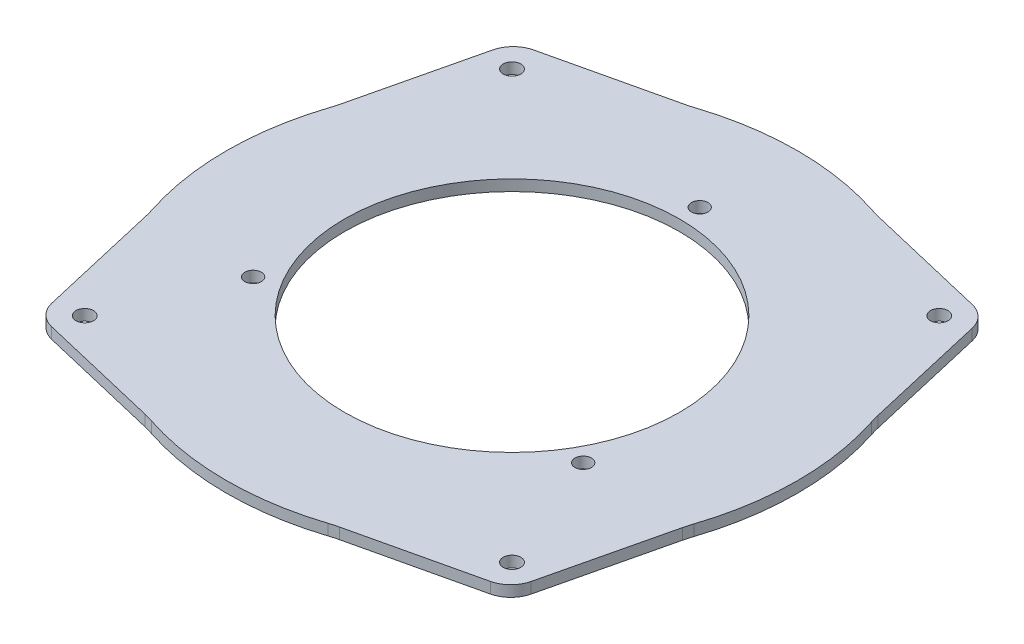
SolidWorks part; units mm, degrees
ref_plane "Front Plane" through (0, 0, 0) normal (0, 0, 1) x (1, 0, 0)
ref_plane "Top Plane" through (0, 0, 0) normal (0, 1, 0) x (1, 0, 0)
ref_plane "Right Plane" through (0, 0, 0) normal (1, 0, 0) x (0, 0, -1)
sketch "Sketch1" plane through (0, 0, 0) normal (0, 1, 0) x (1, 0, 0)
  line L0 (49.872, -261.8935) -> (473.872, -261.8935) construction
  line L1 (17.8971, 48.9297) -> (40.1493, 43.6512)
  line L2 (43.8664, 39.9141) -> (49.0252, 17.6338)
  line L3 (48.9297, -17.8971) -> (43.6512, -40.1493)
  line L4 (39.9141, -43.8664) -> (17.6338, -49.0252)
  line L5 (-17.8971, -48.9297) -> (-40.1493, -43.6512)
  line L6 (-43.8664, -39.9141) -> (-49.0252, -17.6338)
  line L7 (-48.9297, 17.8971) -> (-43.6512, 40.1493)
  line L8 (-39.9141, 43.8664) -> (-17.6338, 49.0252)
  line L9 (0, 38.8907) -> (0, -38.8907) construction
  line L10 (-38.8907, 0) -> (38.8907, 0) construction
  line L11 (0, 34.174) -> (-29.6727, -17.4567) construction
  line L12 (-38.8907, 38.8907) -> (38.8907, 38.8907) construction
  line L13 (-38.8907, 38.8907) -> (-38.8907, -38.8907) construction
  line L14 (-38.8907, -38.8907) -> (38.8907, -38.8907) construction
  line L15 (38.8907, 38.8907) -> (38.8907, -38.8907) construction
  line L16 (-29.6727, -17.4567) -> (29.6727, -16.7173) construction
  line L17 (29.6727, -16.7173) -> (0, 34.174) construction
  line L18 (0, 34.174) -> (0, -17.087) construction
  line L19 (-29.6727, -17.4567) -> (14.8363, 8.7284) construction
  circle A0 centre (0, 0) radius 30 construction
  arc A1 (-17.6338, 49.0252) -> (-15.9939, 49.4792) centre (-22.1454, 68.5097) ccw
  arc A2 (0.1397, 51.9998) -> (-15.9939, 49.4792) centre (0, 0) ccw
  arc A3 (16.2596, 49.3926) -> (0.1397, 51.9998) centre (0, 0) ccw
  arc A4 (16.2596, 49.3926) -> (17.8971, 48.9297) centre (22.5132, 68.3897) ccw
  arc A5 (43.8664, 39.9141) -> (40.1493, 43.6512) centre (38.9952, 38.7862) ccw
  arc A6 (49.0252, 17.6338) -> (49.4792, 15.9939) centre (68.5097, 22.1454) ccw
  arc A7 (49.3926, -16.2596) -> (49.4792, 15.9939) centre (0, 0) ccw
  arc A8 (49.3926, -16.2596) -> (48.9297, -17.8971) centre (68.3897, -22.5132) ccw
  arc A9 (39.9141, -43.8664) -> (43.6512, -40.1493) centre (38.7862, -38.9952) ccw
  arc A10 (17.6338, -49.0252) -> (15.9939, -49.4792) centre (22.1454, -68.5097) ccw
  arc A11 (-16.2596, -49.3926) -> (15.9939, -49.4792) centre (0, 0) ccw
  arc A12 (-16.2596, -49.3926) -> (-17.8971, -48.9297) centre (-22.5132, -68.3897) ccw
  arc A13 (-43.8664, -39.9141) -> (-40.1493, -43.6512) centre (-38.9952, -38.7862) ccw
  arc A14 (-49.0252, -17.6338) -> (-49.4792, -15.9939) centre (-68.5097, -22.1454) ccw
  arc A15 (-49.3926, 16.2596) -> (-49.4792, -15.9939) centre (0, 0) ccw
  arc A16 (-49.3926, 16.2596) -> (-48.9297, 17.8971) centre (-68.3897, 22.5132) ccw
  arc A17 (-39.9141, 43.8664) -> (-43.6512, 40.1493) centre (-38.7862, 38.9952) ccw
  circle A18 centre (-38.8907, 38.8907) radius 1.6
  circle A19 centre (38.8907, 38.8907) radius 1.6
  circle A20 centre (38.8907, -38.8907) radius 1.6
  circle A21 centre (-38.8907, -38.8907) radius 1.6
  circle A22 centre (0, 0) radius 30.5
  circle A24 centre (0, 34.174) radius 1.5
  circle A25 centre (-29.6727, -17.4567) radius 1.5
  circle A26 centre (29.6727, -16.7173) radius 1.5
  circle A27 centre (0, 34.174) radius 2.675 construction
  circle A28 centre (-29.6727, -17.4567) radius 2.675 construction
  circle A29 centre (29.6727, -16.7173) radius 2.675 construction
  point P22 (0, 0)
  point P65 (0, 0)
  point P69 (0, 0)
  point P70 (0, 0)
  point P73 (0, 0)
  point P74 (0, 0)
  point P75 (0, 0)
  point P76 (0, 0)
  dimension "D1" = 3.2
  dimension "D2" = 60
  dimension "D3" = 61
  dimension "D4" = 3
  dimension "D5" = 5.35
  dimension "D6" = 64.26
  dimension "D7" = 64.7
  dimension "D8" = 64.9
extrude "Boss-Extrude1" add sketch "Sketch1" along normal blind 2
